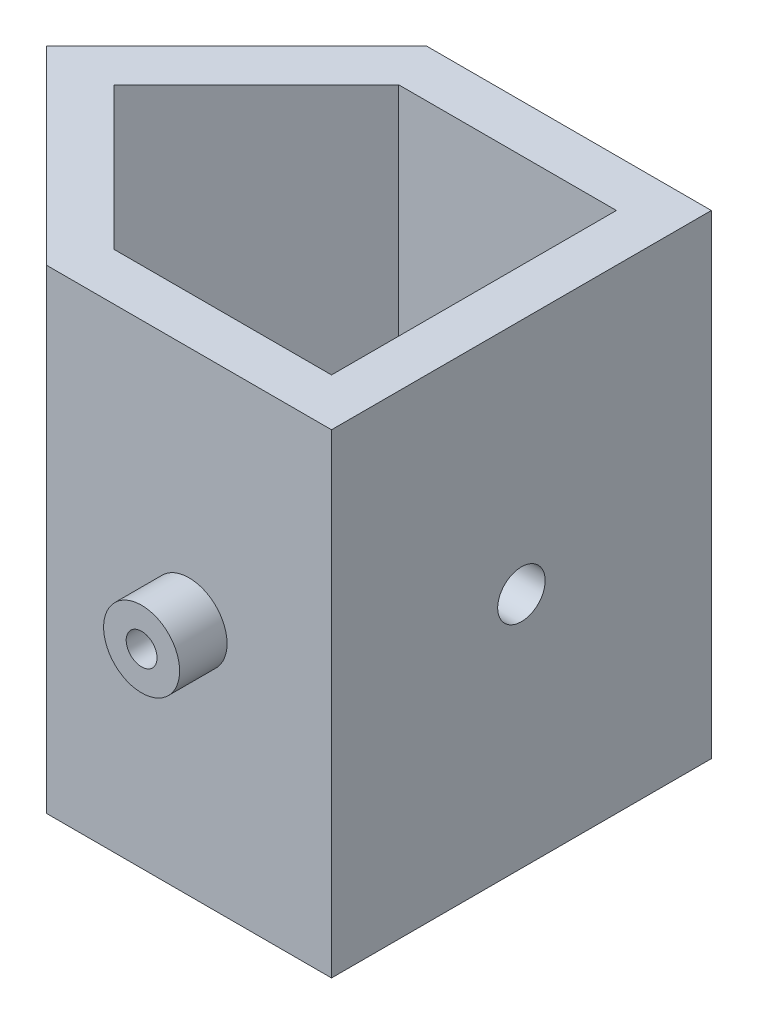
SolidWorks part; units mm, degrees
ref_plane "Alzado" through (0, 0, 0) normal (0, 0, 1) x (1, 0, 0)
ref_plane "Planta" through (0, 0, 0) normal (0, 1, 0) x (1, 0, 0)
ref_plane "Vista lateral" through (0, 0, 0) normal (1, 0, 0) x (0, 0, -1)
sketch "Croquis3" plane through (0, 0, 0) normal (0, 1, 0) x (1, 0, 0)
  line L0 (0, 0) -> (20, 20)
  line L1 (20, 20) -> (50, 20)
  line L2 (50, 20) -> (50, -20)
  line L3 (50, -20) -> (20, -20)
  line L4 (20, -20) -> (0, 0)
  line L5 (7.0711, 0) -> (22.0711, 15)
  line L6 (22.0711, 15) -> (45, 15)
  line L7 (45, 15) -> (45, -15)
  line L8 (45, -15) -> (22.0711, -15)
  line L9 (22.0711, -15) -> (7.0711, 0)
  point P12 (14.5711, 7.5)
  point P14 (50, 0)
  dimension "D1" = 28.2843
  dimension "D2" = 28.2843
  dimension "D3" = 30
  dimension "D4" = 30
  dimension "D5" = 40
  dimension "D6" = 5
  dimension "D7" = 30
  dimension "D8" = 5
  dimension "D9" = 5
  dimension "D10" = 21.2132
  dimension "D11" = 21.2132
  dimension "D12" = 42.9289
extrude "Saliente-Extruir1" add sketch "Croquis3" along normal blind 50 contours L9 L5 L6 L7 L8 | L0 L1 L2 L3 L4
sketch "Croquis7" plane through (50, 0, 0) normal (1, 0, 0) x (0, 0, -1)
  line L0 (20, 50) -> (20, 0) construction
  circle A0 centre (0, 25) radius 2.5
  point P5 (20, 25)
  dimension "D1" = 25
  dimension "D3" = 5
  dimension "D2" = 20
extrude "Cortar-Extruir1" cut sketch "Croquis7" against normal blind 5 contours A0
sketch "Croquis8" plane through (0, 0, 20) normal (0, 0, 1) x (1, 0, 0)
  line L0 (50, 0) -> (20, 0) construction
  line L1 (50, 50) -> (50, 0) construction
  circle A0 centre (35, 25) radius 4
  point P4 (35, 0)
  dimension "D1" = 8
  dimension "D2" = 25
  dimension "D3" = 15
extrude "Saliente-Extruir2" add sketch "Croquis8" along normal blind 5
sketch "Croquis15" plane through (0, 0, -20) normal (0, 0, -1) x (-1, 0, 0)
  line L0 (-20, 0) -> (-50, 0) construction
  line L1 (-50, 50) -> (-50, 0) construction
  circle A0 centre (-35, 25) radius 4
  dimension "D1" = 8
  dimension "D2" = 25
  dimension "D3" = 15
extrude "Saliente-Extruir3" add sketch "Croquis15" along normal blind 5 contours A0
sketch "Croquis16" plane through (0, 0, -25) normal (0, 0, -1) x (-1, 0, 0)
  circle A0 centre (-35, 25) radius 1.625
  dimension "D1" = 3.25
sketch "Croquis17" plane through (0, 0, 25) normal (0, 0, 1) x (1, 0, 0)
  circle A0 centre (35, 25) radius 1.625
  dimension "D1" = 3.25
extrude "Cortar-Extruir4" cut sketch "Croquis17" against normal blind 6 contours A0
extrude "Cortar-Extruir5" cut sketch "Croquis16" against normal blind 6 contours A0
